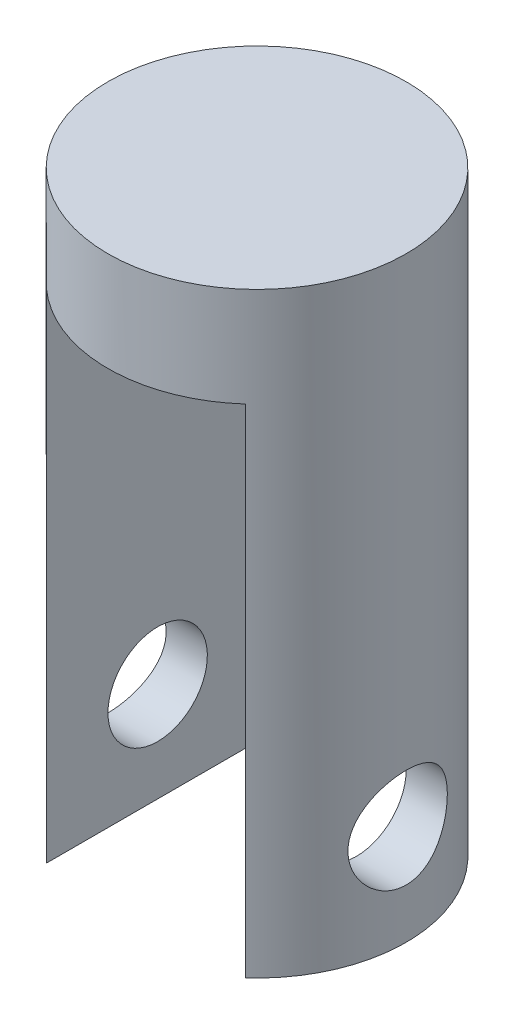
SolidWorks part; units mm, degrees
ref_plane "Ebene vorne" through (0, 0, 0) normal (0, 0, 1) x (1, 0, 0)
ref_plane "Ebene oben" through (0, 0, 0) normal (0, 1, 0) x (1, 0, 0)
ref_plane "Ebene rechts" through (0, 0, 0) normal (1, 0, 0) x (0, 0, -1)
sketch "Skizze1" plane through (0, 0, 0) normal (0, 1, 0) x (1, 0, 0)
  circle A0 centre (0, 0) radius 15
  dimension "D1" = 30
extrude "Aufsatz-Linear austragen1" add sketch "Skizze1" along normal blind 10
sketch "Skizze4" plane through (0, 0, 0) normal (0, 1, 0) x (1, 0, 0)
  circle A0 centre (0, 0) radius 15
  circle A2 centre (0, 0) radius 15 construction
extrude "Aufsatz-Linear austragen3" add sketch "Skizze4" against normal blind 50
sketch "Skizze5" plane through (0, 0, 0) normal (0, 0, 1) x (1, 0, 0)
  line L0 (-15, -50) -> (15, -50) construction
  line L1 (-10, -50) -> (10, -50)
  line L2 (-10, -50) -> (-10, 0)
  line L3 (-10, 0) -> (10, 0)
  line L4 (10, -50) -> (10, 0)
  dimension "D1" = 20
extrude "Schnitt-Linear austragen1" cut sketch "Skizze5" against normal through all both and the other way through all
sketch "Skizze6" plane through (0, 0, 0) normal (1, 0, 0) x (0, 0, -1)
  line L0 (0, 0) -> (0, -40) construction
  circle A0 centre (0, -40) radius 5
  dimension "D2" = 10
  dimension "D1" = 40
extrude "Schnitt-Linear austragen2" cut sketch "Skizze6" against normal through all both and the other way through all
